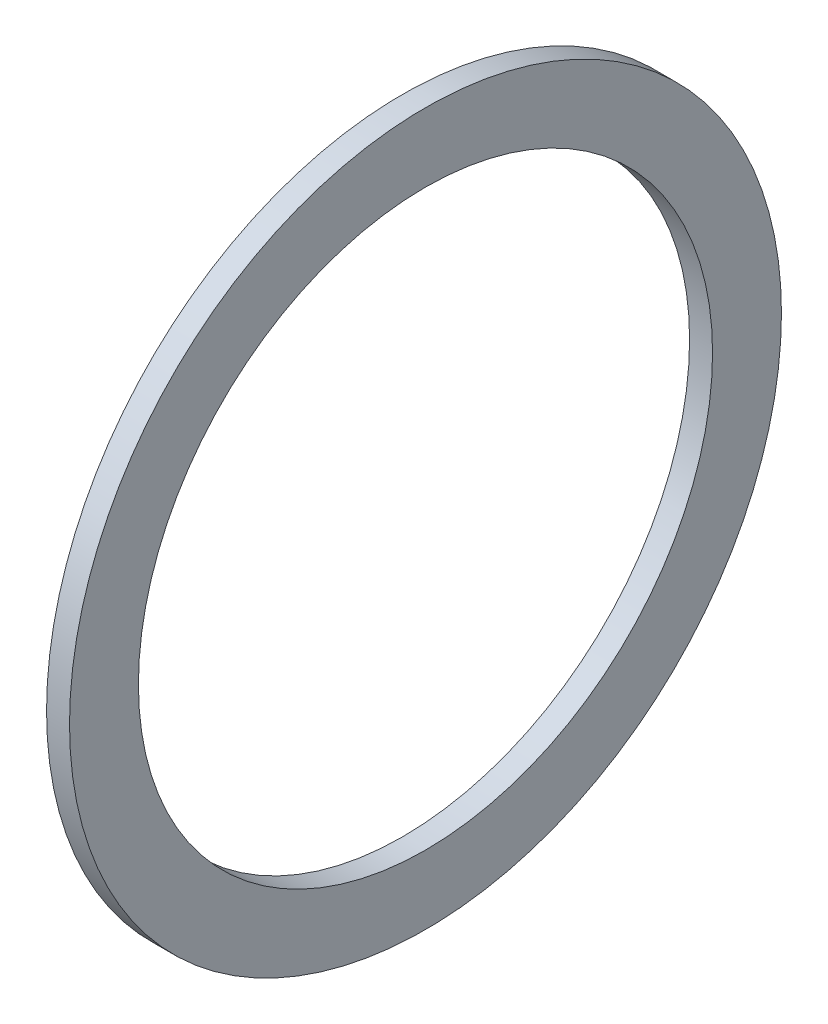
SolidWorks part; units mm, degrees
material "6061-T6 (SS)"
ref_plane "Front" through (0, 0, 0) normal (0, 0, 1) x (1, 0, 0)
ref_plane "Top" through (0, 0, 0) normal (0, 1, 0) x (1, 0, 0)
ref_plane "Right" through (0, 0, 0) normal (1, 0, 0) x (0, 0, -1)
sketch "Sketch2" plane through (0, 0, 0) normal (1, 0, 0) x (0, 0, -1)
  circle A0 centre (0, 0) radius 49.2125
  circle A1 centre (0, 0) radius 39.6875
  dimension "D1" = 98.425
  dimension "D2" = 79.375
extrude "Boss-Extrude1" add sketch "Sketch2" along normal mid plane 3.175
